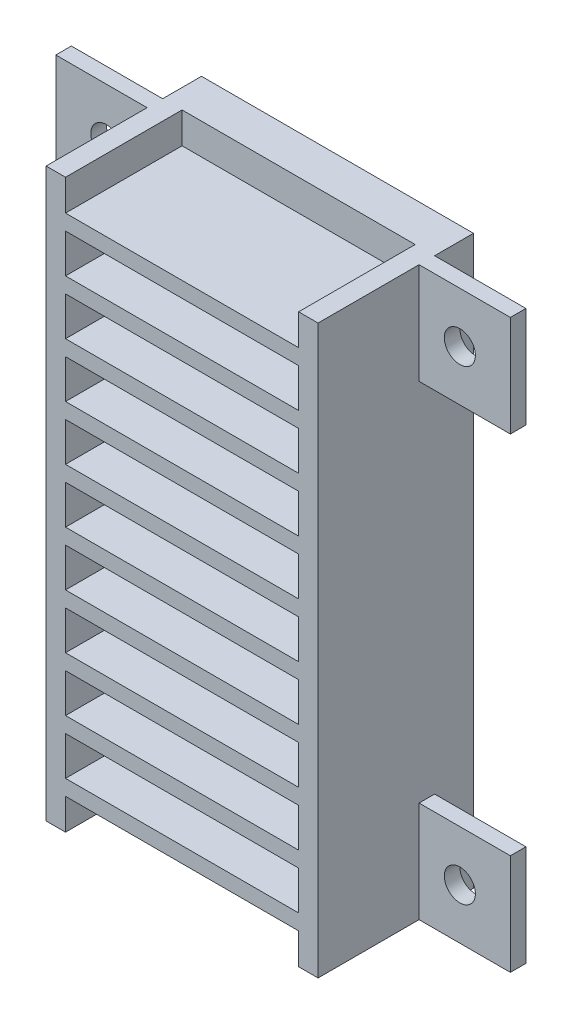
SolidWorks part; units mm, degrees
ref_plane "Front Plane" through (0, 0, 0) normal (0, 0, 1) x (1, 0, 0)
ref_plane "Top Plane" through (0, 0, 0) normal (0, 1, 0) x (1, 0, 0)
ref_plane "Right Plane" through (0, 0, 0) normal (1, 0, 0) x (0, 0, -1)
sketch "Sketch1" plane through (0, 0, 0) normal (0, 0, 1) x (1, 0, 0)
  line L0 (0, 73) -> (0, 0) construction
  line L1 (-17.5, 0) -> (17.5, 0)
  line L2 (-17.5, 0) -> (-17.5, 73)
  line L3 (-17.5, 73) -> (17.5, 73)
  line L4 (17.5, 0) -> (17.5, 73)
  line L5 (-17.5, 61) -> (17.5, 61) construction
  line L6 (-15, 67) -> (15, 67)
  line L7 (-15, 67) -> (-15, 62)
  line L8 (-15, 62) -> (15, 62)
  line L9 (15, 67) -> (15, 62)
  line L10 (-15, 60) -> (15, 60)
  line L11 (15, 55) -> (15, 60)
  line L12 (-15, 55) -> (15, 55)
  line L13 (-15, 55) -> (-15, 60)
  line L14 (-17.5, 54) -> (17.5, 54) construction
  line L15 (-15, 53) -> (-15, 48)
  line L16 (-15, 53) -> (15, 53)
  line L17 (15, 53) -> (15, 48)
  line L18 (-15, 48) -> (15, 48)
  line L19 (-15, 46) -> (15, 46)
  line L20 (15, 41) -> (15, 46)
  line L21 (-15, 41) -> (15, 41)
  line L22 (-15, 41) -> (-15, 46)
  line L23 (-17.5, 40) -> (17.5, 40) construction
  line L24 (-15, 39) -> (-15, 34)
  line L25 (-15, 39) -> (15, 39)
  line L26 (15, 39) -> (15, 34)
  line L27 (-15, 34) -> (15, 34)
  line L28 (-15, 27) -> (15, 27)
  line L29 (15, 27) -> (15, 32)
  line L30 (-15, 32) -> (15, 32)
  line L31 (-15, 27) -> (-15, 32)
  line L32 (-15, 25) -> (-15, 20)
  line L33 (-15, 25) -> (15, 25)
  line L34 (15, 25) -> (15, 20)
  line L35 (-15, 20) -> (15, 20)
  line L36 (-15, 18) -> (15, 18)
  line L37 (15, 13) -> (15, 18)
  line L38 (-15, 13) -> (15, 13)
  line L39 (-15, 13) -> (-15, 18)
  line L40 (-17.5, 12) -> (17.5, 12) construction
  line L41 (-15, 11) -> (-15, 6)
  line L42 (-15, 11) -> (15, 11)
  line L43 (15, 11) -> (15, 6)
  line L44 (-15, 6) -> (15, 6)
  point P5 (0, 0)
  dimension "D1" = 73
  dimension "D2" = 35
  dimension "D3" = 6
  dimension "D4" = 5
  dimension "D5" = 30
  dimension "D6" = 1
  dimension "D7" = 1
  dimension "D8" = 1
  dimension "D9" = 1
extrude "Boss-Extrude1" add sketch "Sketch1" along normal blind 5
ref_plane "Plane1" through (0, 0, 0) normal (0, 0, -1) x (-1, 0, 0)
sketch "Sketch2" plane through (0, 0, 0) normal (0, 0, -1) x (-1, 0, 0)
  line L0 (-15, 41) -> (-15, 39) construction
  line L1 (-15, 39) -> (15, 39) construction
  line L2 (15, 39) -> (15, 41) construction
  line L3 (15, 41) -> (-15, 41) construction
  line L4 (0, 41) -> (0, 39) construction
  line L5 (-4.05, 41) -> (-4.05, 39)
  line L6 (-4.05, 39) -> (-2.05, 39)
  line L7 (-2.05, 39) -> (-2.05, 41)
  line L8 (-2.05, 41) -> (-4.05, 41)
  line L9 (2.05, 39) -> (2.05, 41)
  line L10 (4.05, 39) -> (2.05, 39)
  line L11 (4.05, 41) -> (4.05, 39)
  line L12 (2.05, 41) -> (4.05, 41)
  line L13 (-15, 55) -> (-15, 53) construction
  line L14 (-15, 53) -> (15, 53) construction
  line L15 (15, 53) -> (15, 55) construction
  line L16 (15, 55) -> (-15, 55) construction
  line L17 (0, 55) -> (0, 53) construction
  line L18 (-4.05, 55) -> (-4.05, 53)
  line L19 (-4.05, 53) -> (-2.05, 53)
  line L20 (-2.05, 53) -> (-2.05, 55)
  line L21 (-2.05, 55) -> (-4.05, 55)
  line L22 (2.05, 53) -> (2.05, 55)
  line L23 (4.05, 53) -> (2.05, 53)
  line L24 (4.05, 55) -> (4.05, 53)
  line L25 (2.05, 55) -> (4.05, 55)
  line L26 (15, 27) -> (-15, 27) construction
  line L27 (0, 27) -> (0, 25) construction
  line L28 (-15, 25) -> (15, 25) construction
  line L29 (-4.05, 27) -> (-4.05, 25)
  line L30 (-4.05, 25) -> (-2.05, 25)
  line L31 (-2.05, 25) -> (-2.05, 27)
  line L32 (-2.05, 27) -> (-4.05, 27)
  line L33 (2.05, 25) -> (2.05, 27)
  line L34 (4.05, 25) -> (2.05, 25)
  line L35 (4.05, 27) -> (4.05, 25)
  line L36 (2.05, 27) -> (4.05, 27)
  line L37 (0, 13) -> (0, 11) construction
  line L38 (15, 13) -> (-15, 13) construction
  line L39 (-15, 11) -> (15, 11) construction
  line L40 (-4.05, 13) -> (-4.05, 11)
  line L41 (-4.05, 11) -> (-2.05, 11)
  line L42 (-2.05, 11) -> (-2.05, 13)
  line L43 (-2.05, 13) -> (-4.05, 13)
  line L44 (2.05, 11) -> (2.05, 13)
  line L45 (4.05, 11) -> (2.05, 11)
  line L46 (4.05, 13) -> (4.05, 11)
  line L47 (2.05, 13) -> (4.05, 13)
  dimension "D1" = 2.05
  dimension "D2" = 2
  dimension "D3" = 2.05
  dimension "D4" = 2.05
  dimension "D5" = 2.05
extrude "Boss-Extrude2" add sketch "Sketch2" along normal blind 4.1
ref_plane "Plane2" through (0, 0, 5) normal (0, 0, 1) x (1, 0, 0)
sketch "Sketch4" plane through (0, 0, 5) normal (0, 0, 1) x (1, 0, 0)
  line L1 (17.5, 73) -> (-17.5, 73) construction
  line L3 (-29.25, 73) -> (-29.25, 60)
  line L7 (0, 0) -> (0, 73) construction
  line L8 (-16.25, 73) -> (-29.25, 73)
  line L9 (-29.25, 60) -> (-16.25, 60)
  line L12 (-16.25, 66.5) -> (-29.25, 66.5) construction
  line L13 (-17.5, 73) -> (-17.5, 0) construction
  line L14 (-22.75, 73) -> (-22.75, 60) construction
  line L15 (17.5, 36.5) -> (-17.5, 36.5) construction
  line L16 (17.5, 0) -> (17.5, 73) construction
  line L17 (-29.25, 13) -> (-16.25, 13)
  line L19 (-29.25, 0) -> (-29.25, 13)
  line L24 (-16.25, 0) -> (-29.25, 0)
  line L27 (-16.25, 60) -> (-16.25, 73)
  line L29 (-16.25, 13) -> (-16.25, 0)
  line L30 (29.25, 60) -> (16.25, 60)
  line L31 (29.25, 73) -> (29.25, 60)
  line L32 (16.25, 73) -> (29.25, 73)
  line L33 (16.25, 60) -> (16.25, 73)
  line L34 (29.25, 0) -> (29.25, 13)
  line L35 (16.25, 0) -> (29.25, 0)
  line L36 (16.25, 13) -> (16.25, 0)
  line L37 (29.25, 13) -> (16.25, 13)
  circle A0 centre (-22.75, 66.5) radius 2
  circle A10 centre (-22.75, 6.5) radius 2
  circle A11 centre (22.75, 66.5) radius 2
  circle A12 centre (22.75, 6.5) radius 2
  point P29 (-22.75, 66.5)
  dimension "D5" = 4
  dimension "D1" = 1.25
  dimension "D2" = 13
  dimension "D3" = 13
extrude "Boss-Extrude3" add sketch "Sketch4" along normal blind 2
sketch "Sketch7" plane through (0, 0, 0) normal (0, 0, 1) x (1, 0, 0)
  line L0 (16.25, 73) -> (-16.25, 73) construction
  line L1 (-15, 62) -> (15, 62)
  line L2 (-15, 62) -> (-15, 60)
  line L3 (-15, 60) -> (15, 60)
  line L4 (15, 62) -> (15, 60)
  line L5 (-15, 55) -> (15, 55)
  line L6 (-15, 55) -> (-15, 53)
  line L7 (-15, 53) -> (15, 53)
  line L8 (15, 55) -> (15, 53)
  line L9 (-15, 48) -> (15, 48)
  line L10 (-15, 48) -> (-15, 46)
  line L11 (-15, 46) -> (15, 46)
  line L12 (15, 48) -> (15, 46)
  line L13 (-15, 41) -> (15, 41)
  line L14 (-15, 41) -> (-15, 39)
  line L15 (-15, 39) -> (15, 39)
  line L16 (15, 41) -> (15, 39)
  line L17 (-15, 34) -> (15, 34)
  line L18 (-15, 34) -> (-15, 32)
  line L19 (-15, 32) -> (15, 32)
  line L20 (15, 34) -> (15, 32)
  line L21 (-15, 27) -> (15, 27)
  line L22 (-15, 27) -> (-15, 25)
  line L23 (-15, 25) -> (15, 25)
  line L24 (15, 27) -> (15, 25)
  line L25 (-15, 20) -> (15, 20)
  line L26 (-15, 20) -> (-15, 18)
  line L27 (-15, 18) -> (15, 18)
  line L28 (15, 20) -> (15, 18)
  line L29 (-15, 13) -> (15, 13)
  line L30 (-15, 13) -> (-15, 11)
  line L31 (-15, 11) -> (15, 11)
  line L32 (15, 13) -> (15, 11)
  line L33 (-15, 6) -> (15, 6)
  line L34 (-15, 6) -> (-15, 4)
  line L35 (-15, 4) -> (15, 4)
  line L36 (15, 6) -> (15, 4)
  line L37 (-15, 67) -> (15, 67)
  line L38 (-15, 67) -> (-15, 69)
  line L39 (-15, 69) -> (15, 69)
  line L40 (15, 67) -> (15, 69)
  line L41 (15, 73) -> (17.5, 73)
  line L42 (15, 73) -> (15, 0)
  line L43 (15, 0) -> (17.5, 0)
  line L44 (17.5, 73) -> (17.5, 0)
  line L45 (-16.25, 0) -> (16.25, 0) construction
  line L46 (-15, 0) -> (-17.5, 0)
  line L47 (-15, 0) -> (-15, 73)
  line L48 (-15, 73) -> (-17.5, 73)
  line L49 (-17.5, 0) -> (-17.5, 73)
  dimension "D1" = 2
  dimension "D2" = 30
  dimension "D3" = 30
  dimension "D4" = 2
  dimension "D5" = 2.5
  dimension "D6" = 2.5
extrude "Boss-Extrude4" add sketch "Sketch7" along normal blind 20 contours L4 L1 L2 L3 | L37 L40 L39 L38 | L8 L5 L6 L7 | L12 L9 L10 L11 | L16 L13 L14 L15 | L20 L17 L18 L19 | L24 L21 L22 L23 | L49 L46 L47 L34 L30 L26 L22 L18 L14 L10 L6 L2 L38 L48 | L44 L43 L42 L41
